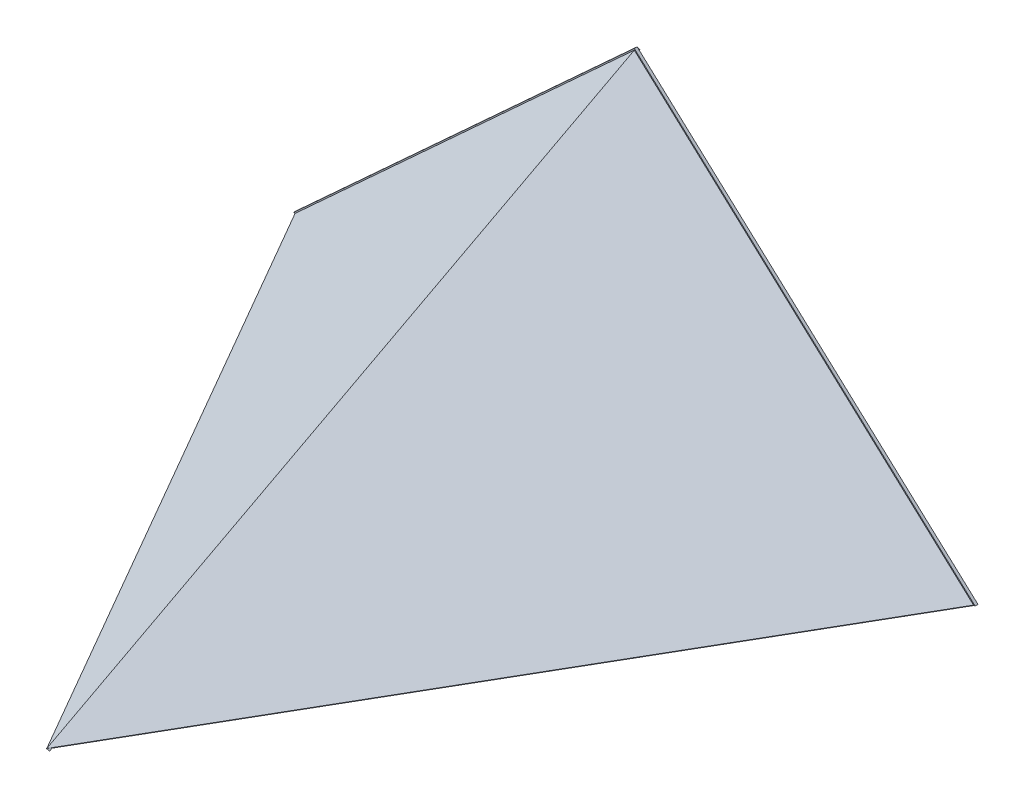
SolidWorks part; units mm, degrees
ref_plane "Front Plane" through (0, 0, 0) normal (0, 0, 1) x (1, 0, 0)
ref_plane "Top Plane" through (0, 0, 0) normal (0, 1, 0) x (1, 0, 0)
ref_plane "Right Plane" through (0, 0, 0) normal (1, 0, 0) x (0, 0, -1)
sketch "Sketch1" plane through (0, 0, 0) normal (0, 0, 1) x (1, 0, 0)
  line L0 (0, 0) -> (304.8, 0)
  line L1 (304.8, 0) -> (0, 279.4)
  line L2 (0, 279.4) -> (-304.8, 0)
  line L3 (-304.8, 0) -> (0, 0)
  dimension "D1" = 304.8
  dimension "D2" = 304.8
  dimension "D3" = 279.4
ref_plane "Plane3" through (0, 0, 0) normal (0, 0, 1) x (1, 0, 0)
ref_plane "Plane4" through (0, 0, 0) normal (0, -1, 0) x (1, 0, 0)
sketch "Sketch4" plane through (0, 0, 0) normal (0, -1, 0) x (1, 0, 0)
  line L0 (-304.8, 0) -> (0, 527.9291)
  line L1 (0, 527.9291) -> (304.8, 0)
  line L2 (-304.8, 0) -> (0, 0) construction
  dimension "D1" = 60
ref_plane "Plane5" through (-120.7886, 131.7694, 69.7374) normal (0.6295, -0.6867, -0.3635) x (-0.7587, -0.4425, -0.4781)
ref_plane "Plane6" through (120.7886, 131.7694, 69.7374) normal (-0.6295, -0.6867, -0.3635) x (-0.7587, 0.4425, 0.4781)
sketch "Sketch6" plane through (120.7886, 131.7694, 69.7374) normal (-0.6295, -0.6867, -0.3635) x (-0.7587, 0.4425, 0.4781)
  line L0 (-231.2574, -51.0557) -> (252.3953, -422.1248)
  line L1 (252.3953, -422.1248) -> (123.6264, 161.135)
  line L2 (123.6264, 161.135) -> (-231.2574, -51.0557)
extrude "Boss-Extrude1" add sketch "Sketch6" along normal blind 2.54
sketch "Sketch7" plane through (-120.7886, 131.7694, 69.7374) normal (0.6295, -0.6867, -0.3635) x (-0.7587, -0.4425, -0.4781)
  line L0 (231.2574, -51.0557) -> (-252.3953, -422.1248)
  line L1 (-252.3953, -422.1248) -> (-123.6264, 161.135)
  line L2 (-123.6264, 161.135) -> (231.2574, -51.0557)
extrude "Boss-Extrude2" add sketch "Sketch7" along normal blind 2.54
sketch "Sketch8" plane through (120.7886, 131.7694, 69.7374) normal (0.6295, 0.6867, 0.3635) x (0.777, -0.5564, -0.2945)
  line L0 (-155.4574, 130.6943) -> (-155.4574, -292.3969)
  line L1 (-155.4574, -466.6109) -> (-155.4574, 130.6943) construction
  line L2 (-155.4574, -292.3969) -> (122.4102, 38.1192)
  line L3 (236.8262, 0) -> (-155.4574, 130.6943) construction
  line L4 (122.4102, 38.1192) -> (-155.4574, 130.6943)
  line L5 (-155.4574, -466.6109) -> (236.8262, 0) construction
  dimension "D1" = 431.8
ref_plane "Plane7" through (0, 0, 0) normal (0, 0, 1) x (1, 0, 0)
sketch "Sketch9" plane through (0, 0, 0) normal (0, 0, 1) x (1, 0, 0)
  line L0 (0, 279.4) -> (304.8, 0)
  line L1 (304.8, 0) -> (-304.8, 0)
  line L2 (-304.8, 0) -> (0, 279.4)
extrude "Boss-Extrude3" add sketch "Sketch9" along normal blind 2.54
ref_plane "Plane8" through (0, 81.4917, 0) normal (0, -1, 0) x (0.5, 0, -0.866)
sketch "Sketch10" plane through (0, 81.4917, 0) normal (0, -1, 0) x (0.5, 0, -0.866)
  line L0 (-323.85, 186.9749) -> (-107.95, -186.9749)
  line L1 (0, 0) -> (-152.4, -263.9645) construction
  line L2 (-107.95, -186.9749) -> (107.95, 186.9749)
  line L3 (-323.85, 186.9749) -> (107.95, 186.9749) construction
